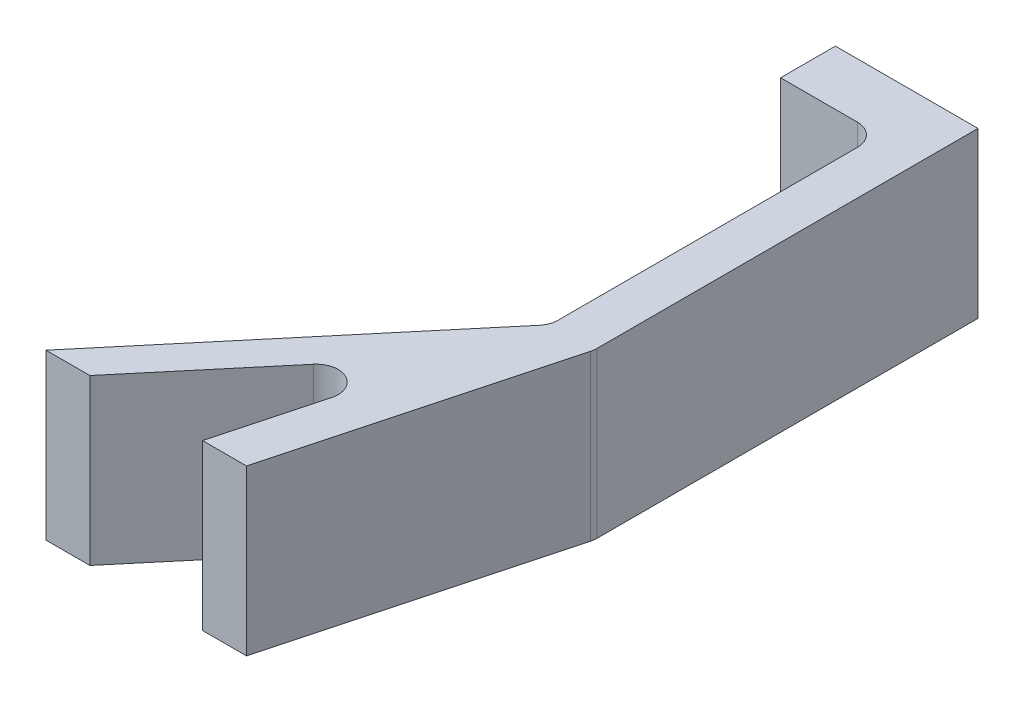
SolidWorks part; units mm, degrees
material "ABS PC"
ref_plane "Front Plane" through (0, 0, 0) normal (0, 0, 1) x (1, 0, 0)
ref_plane "Top Plane" through (0, 0, 0) normal (0, 1, 0) x (1, 0, 0)
ref_plane "Right Plane" through (0, 0, 0) normal (1, 0, 0) x (0, 0, -1)
sketch "Sketch1" plane through (0, 0, 0) normal (0, 1, 0) x (1, 0, 0)
  line L0 (0, 355.2663) -> (0, 0) construction
  line L1 (-486.7902, 0) -> (453.4144, 0) construction
  line L2 (0, 0) -> (-2, 0) construction
  line L3 (-2, 0) -> (-2, 30)
  line L4 (0, 0) -> (2, 0) construction
  line L5 (2, 0) -> (2, 30)
  line L6 (-2, 30) -> (2, 30) construction
  line L7 (0, 0) -> (-36.9122, -43.9902) construction
  line L8 (-2, 0) -> (-22.9775, -25)
  line L9 (0, -7.4641) -> (0, -25) construction
  line L10 (0, -25) -> (-52.3028, -25) construction
  line L11 (0, -7.4641) -> (0, -454.0905) construction
  line L12 (-22.9775, -25) -> (-18.9775, -25)
  line L13 (-2, 30) -> (-11, 30)
  line L14 (-11, 30) -> (-11, 35)
  line L15 (-11, 35) -> (2, 35)
  line L16 (2, 35) -> (2, 30)
  line L17 (0, 0) -> (-6.6987, -25) construction
  line L18 (-3.8766, -7.0034) -> (-8.6987, -25)
  line L19 (2, 0) -> (-4.6987, -25)
  line L20 (-8.6987, -25) -> (-4.6987, -25)
  line L21 (-3.8766, -7.0034) -> (-18.9775, -25)
  point P0 (0, 0)
  dimension "D1" = 2
  dimension "D2" = 2
  dimension "D3" = 30
  dimension "D4" = 30
  dimension "D5" = 50
  dimension "D6" = 25
  dimension "D7" = 5
  dimension "D8" = 13
  dimension "D9" = 15
  dimension "D10" = 7.0034
  dimension "D11" = 3.8766
extrude "Boss-Extrude1" add sketch "Sketch1" along normal blind 15
sketch "Sketch3" plane through (0, 0, -35) normal (0, 0, -1) x (-1, 0, 0)
  line L0 (11, 15) -> (11, 0)
  line L1 (11, 15) -> (3.5, 15)
  line L2 (11, 0) -> (3.5, 0)
  line L3 (3.5, 15) -> (3.5, 0)
  line L4 (3.5, 0) -> (11, 15) construction
  circle A0 centre (7.25, 7.5) radius 1.6
  dimension "D2" = 3.2
  dimension "D1" = 7.5
extrude "Cut-Extrude2" cut sketch "Sketch3" against normal blind 10 contours L4 A0 | A0 L4
fillet "Fillet2" radius 2 4 edges at (2, 7.5, 0) (-3.8766, 7.5, 7.0034) (-2, 7.5, 0) (-2, 7.5, -30)
